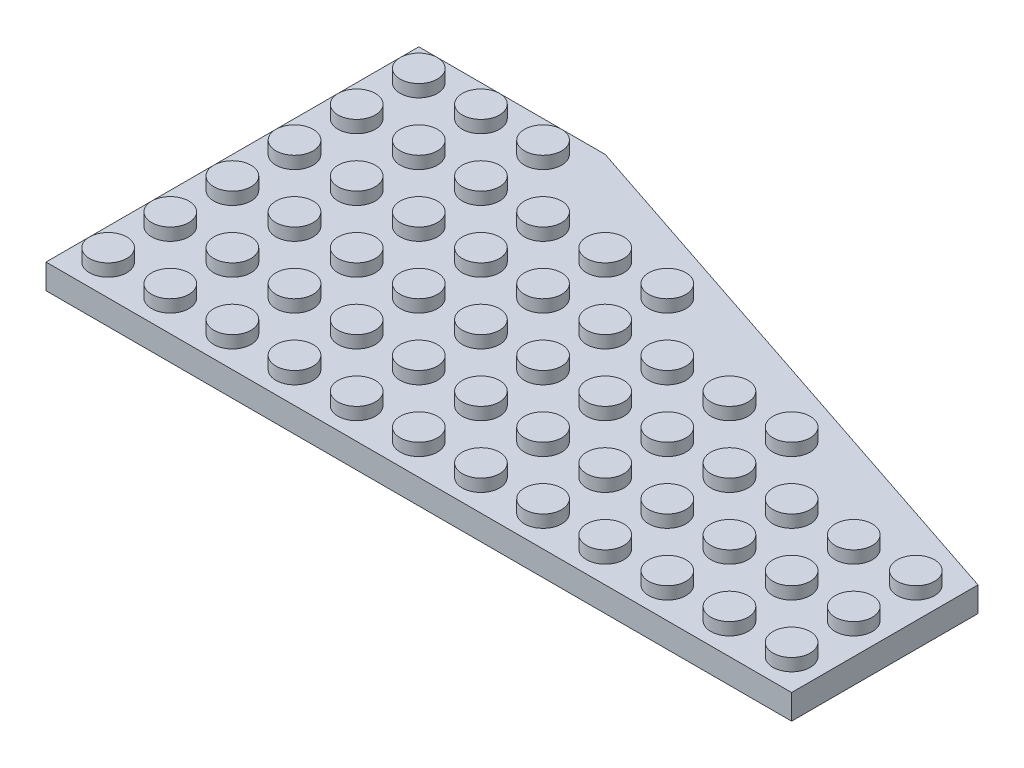
SolidWorks part; units mm, degrees
ref_plane "Front Plane" through (0, 0, 0) normal (0, 0, 1) x (1, 0, 0)
ref_plane "Top Plane" through (0, 0, 0) normal (0, 1, 0) x (1, 0, 0)
ref_plane "Right Plane" through (0, 0, 0) normal (1, 0, 0) x (0, 0, -1)
sketch "Sketch1" plane through (0, 0, 0) normal (0, 1, 0) x (1, 0, 0)
  line L0 (0, 0) -> (96, 0)
  line L1 (96, 0) -> (96, 24)
  line L2 (96, 24) -> (24, 48)
  line L3 (24, 48) -> (0, 48)
  line L4 (0, 48) -> (0, 0)
  dimension "D1" = 24
  dimension "D2" = 96
  dimension "D3" = 48
  dimension "D4" = 24
extrude "Boss-Extrude1" add sketch "Sketch1" along normal blind 3.2
sketch "Sketch2" plane through (0, 3.2, 0) normal (0, 1, 0) x (1, 0, 0)
  line L0 (0, 0) -> (4, 0) construction
  line L1 (0, 0) -> (96, 0) construction
  line L2 (4, 0) -> (4, 4) construction
  circle A0 centre (4, 4) radius 2.4
  dimension "D3" = 4.8
  dimension "D1" = 4
  dimension "D2" = 4
extrude "Boss-Extrude2" add sketch "Sketch2" along normal blind 1.6
pattern_linear "LPattern1" count 6 spacing 8 along (0, 0, -1) count 3 spacing 8 along (1, 0, 0) of "Boss-Extrude2"
sketch "Sketch3" plane through (0, 3.2, 0) normal (0, 1, 0) x (1, 0, 0)
  line L0 (20, 4) -> (28, 4) construction
  circle A0 centre (28, 4) radius 2.4
  dimension "D2" = 4.8
  dimension "D1" = 8
extrude "Boss-Extrude3" add sketch "Sketch3" along normal blind 1.6
pattern_linear "LPattern2" count 3 spacing 8 along (1, 0, 0) count 5 spacing 8 along (0, 0, -1) of "Boss-Extrude3"
sketch "Sketch4" plane through (0, 3.2, 0) normal (0, 1, 0) x (1, 0, 0)
  line L0 (44, 4) -> (52, 4) construction
  circle A0 centre (52, 4) radius 2.4
  dimension "D2" = 4.8
  dimension "D1" = 8
extrude "Boss-Extrude4" add sketch "Sketch4" along normal blind 1.6
pattern_linear "LPattern3" count 3 spacing 8 along (1, 0, 0) count 4 spacing 8 along (0, 0, -1) of "Boss-Extrude4"
sketch "Sketch5" plane through (0, 3.2, 0) normal (0, 1, 0) x (1, 0, 0)
  line L0 (68, 4) -> (76, 4) construction
  circle A0 centre (76, 4) radius 2.4
  dimension "D2" = 4.8
  dimension "D1" = 8
extrude "Boss-Extrude5" add sketch "Sketch5" along normal blind 1.6
pattern_linear "LPattern4" count 3 spacing 8 along (1, 0, 0) count 3 spacing 8 along (0, 0, -1) of "Boss-Extrude5"
shell "Shell1" thickness 1.6
